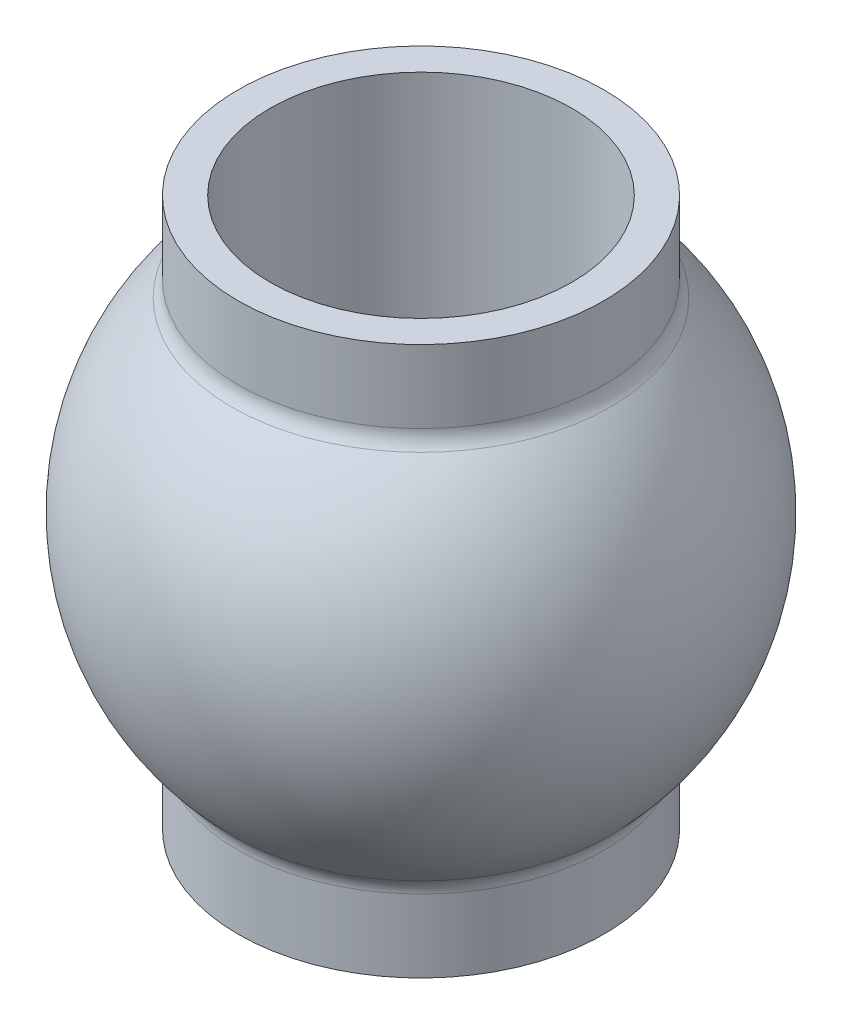
SolidWorks part; units mm, degrees
ref_plane "Front Plane" through (0, 0, 0) normal (0, 0, 1) x (1, 0, 0)
ref_plane "Top Plane" through (0, 0, 0) normal (0, 1, 0) x (1, 0, 0)
ref_plane "Right Plane" through (0, 0, 0) normal (1, 0, 0) x (0, 0, -1)
sketch "Sketch1" plane through (0, 0, 0) normal (0, 0, 1) x (1, 0, 0)
  line L0 (0, 4.1836) -> (0, -4.305) construction
  line L1 (0, 3) -> (2, 3)
  line L2 (2, 3) -> (2, 2.1)
  line L3 (2, -3) -> (0, -3)
  line L4 (0, 3) -> (0, -3)
  line L5 (2, -2.1) -> (2, -3)
  arc A0 (2, 2.1) -> (2, -2.1) centre (0, 0) cw
  dimension "D3" = 2.9
  dimension "D1" = 6
  dimension "D2" = 2
revolve "Revolve1" add sketch "Sketch1" angle 360 about L0
sketch "Sketch2" plane through (0, 3, 0) normal (0, 1, 0) x (1, 0, 0)
  circle A0 centre (0, 0) radius 1.65
  dimension "D1" = 3.3
extrude "Cut-Extrude1" cut sketch "Sketch2" against normal blind 6
fillet "Fillet1" radius 0.25 2 edges at (0, -2.1, 2) (0, 2.1, 2)
sketch "Sketch3" plane through (0, 0, 0) normal (1, 0, 0) x (0, 0, -1)
  line L0 (0, 0) -> (0, -5.8079) construction
